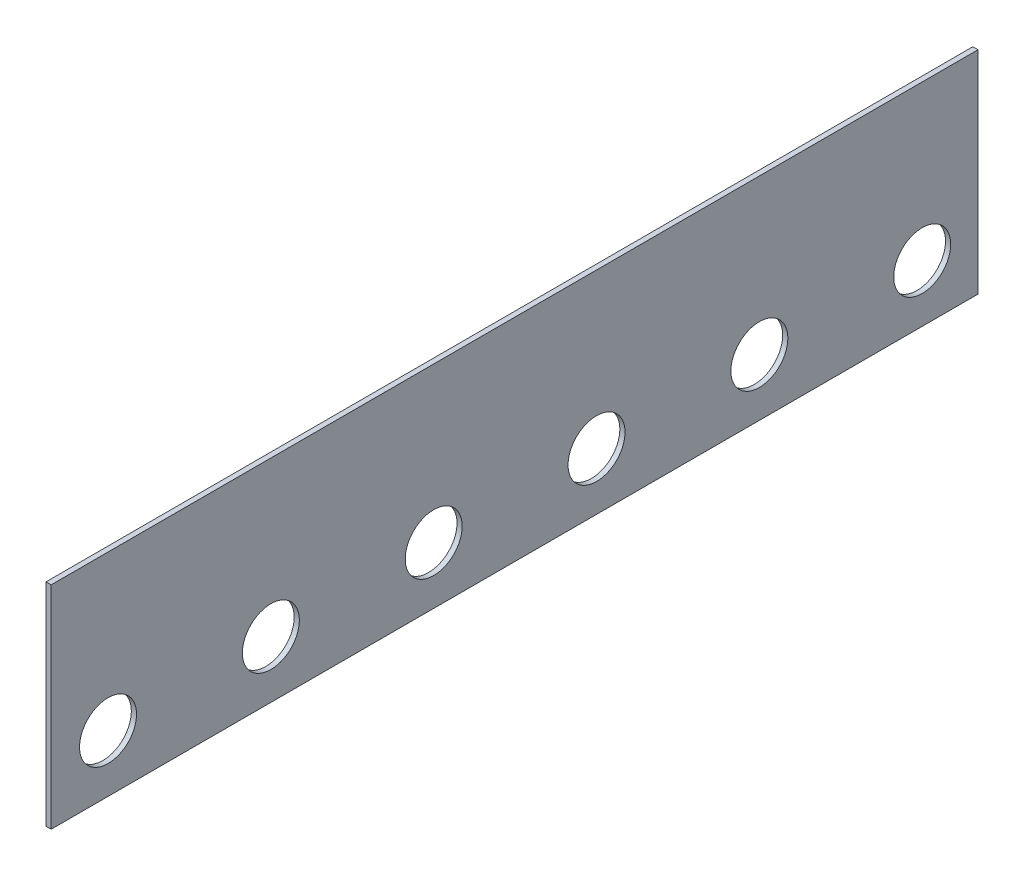
SolidWorks part; units mm, degrees
ref_plane "Front Plane" through (0, 0, 0) normal (0, 0, 1) x (1, 0, 0)
ref_plane "Top Plane" through (0, 0, 0) normal (0, 1, 0) x (1, 0, 0)
ref_plane "Right Plane" through (0, 0, 0) normal (1, 0, 0) x (0, 0, -1)
sketch "Sketch1" plane through (0, 0, 0) normal (1, 0, 0) x (0, 0, -1)
  line L0 (-299.6285, 0) -> (-299.6285, -35)
  line L7 (-299.6285, 95) -> (269.5615, 95)
  line L8 (-265.082, -35) -> (-299.6285, -35)
  line L23 (-264.7097, 0) -> (-265.3749, -51.003) construction
  line L30 (-299.6285, 0) -> (-299.6285, 95)
  line L32 (269.5615, 7.5) -> (269.5615, 95)
  line L36 (-265.1661, -34.999) -> (269.5615, -34.999)
  line L37 (269.5615, 7.5) -> (269.5615, -34.999)
  line L83 (-264.7097, 0) -> (235.3745, 0) construction
  line L147 (0, 0) -> (0, -35) construction
  line L148 (-264.7097, 0) -> (-299.6285, 0) construction
  line L155 (-299.6285, 0) -> (-299.6285, 95) construction
  line L156 (269.5615, 7.5) -> (269.5615, 134.5) construction
  circle A2 centre (-264.7097, 0) radius 17.5
  circle A3 centre (-164.7097, 0) radius 17.5
  circle A4 centre (-64.7097, 0) radius 17.5
  circle A5 centre (35.2903, 0) radius 17.5
  circle A6 centre (135.2903, 0) radius 17.5
  circle A7 centre (235.2903, 0) radius 17.5
  arc A8 (-265.1661, -34.999) -> (-265.082, -35) centre (-264.7097, 0) ccw
  point P0 (0, 0)
  dimension "D5" = 35
  dimension "D4" = 6
extrude "Boss-Extrude1" add sketch "Sketch1" along normal blind 3.175
